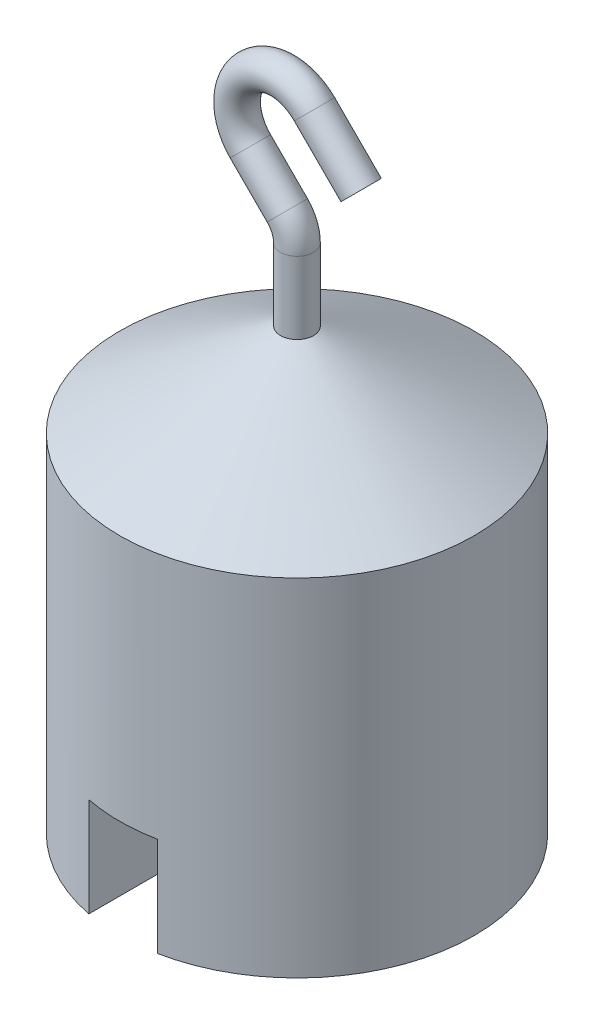
SolidWorks part; units mm, degrees
ref_plane "Front Plane" through (0, 0, 0) normal (0, 0, 1) x (1, 0, 0)
ref_plane "Top Plane" through (0, 0, 0) normal (0, 1, 0) x (1, 0, 0)
ref_plane "Right Plane" through (0, 0, 0) normal (1, 0, 0) x (0, 0, -1)
sketch "Sketch1" plane through (0, 0, 0) normal (0, 0, 1) x (1, 0, 0)
  line L0 (0, 0) -> (0, 42)
  line L1 (0, 42) -> (19.5, 53.2583)
  line L2 (19.5, 53.2583) -> (21.5, 53.2583)
  line L3 (21.5, 53.2583) -> (21.5, 0)
  line L4 (21.5, 0) -> (0, 0)
  dimension "D1" = 42
  dimension "D2" = 2
  dimension "D3" = 120
  dimension "D4" = 21.5
revolve "Revolve1" add sketch "Sketch1" angle 360 about L3
sketch "Sketch2" plane through (0, 53.2583, 0) normal (0, 1, 0) x (1, 0, 0)
  circle A0 centre (21.5, 0) radius 2
  dimension "D1" = 4
sketch "Sketch3" plane through (0, 0, 0) normal (0, 0, 1) x (1, 0, 0)
  line L0 (20.3284, 64.8299) -> (15.8431, 69.3152)
  line L1 (23.5, 53.2583) -> (19.5, 53.2583) construction
  line L2 (23.6213, 77.0934) -> (29.2782, 71.4365)
  line L3 (21.5, 53.2583) -> (21.5, 62.0015)
  arc A0 (15.8431, 69.3152) -> (23.6213, 77.0934) centre (19.7322, 73.2043) cw
  arc A1 (20.3284, 64.8299) -> (21.5, 62.0015) centre (17.5, 62.0015) cw
  point P12 (21.5, 63.6583)
  dimension "D3" = 5.5
  dimension "D6" = 4
  dimension "D1" = 45
  dimension "D2" = 8
  dimension "D4" = 8
  dimension "D5" = 10.4
sweep "Sweep6" add profiles "Sketch2" path "Sketch3"
sketch "Sketch10" plane through (0, 0, 0) normal (0, 0, 1) x (1, 0, 0)
  line L0 (0, 0) -> (43, 0) construction
  line L1 (17.35, 0) -> (25.65, 0)
  line L2 (17.35, 0) -> (17.35, 12)
  line L3 (17.35, 12) -> (25.65, 12)
  line L4 (25.65, 0) -> (25.65, 12)
  line L5 (21.5, 12) -> (21.5, 0) construction
  line L6 (0, 0) -> (43, 0) construction
  point P12 (21.5, 0)
  dimension "D1" = 12
  dimension "D2" = 8.3
extrude "Cut-Extrude1" cut sketch "Sketch10" against normal through all both and the other way through all
sketch "Sketch11" plane through (25.65, 0, 0) normal (-1, 0, 0) x (0, 0, 1)
  line L0 (0, -23.65) -> (0, 23.65) construction
  line L1 (-21.0957, 0) -> (21.0957, 0) construction
  circle A0 centre (0, 4.5) radius 1.5
  dimension "D1" = 3
  dimension "D2" = 4.5
extrude "Boss-Extrude1" add sketch "Sketch11" along normal up to next
sketch "Sketch12" plane through (0, 0, 0) normal (0, 0, 1) x (1, 0, 0)
  line L0 (23.5, 53.2583) -> (44.511, 74.2693) construction
  line L1 (23.5, 53.2583) -> (46.6392, 53.2583) construction
  dimension "D1" = 45
ref_plane "Plane1" through (0, 0, 0) normal (-1, 0, 0) x (0, 0, 1)
sketch "Sketch13" plane through (0, 0, 0) normal (-1, 0, 0) x (0, 0, 1)
  line L0 (0, 27) -> (0, 0) construction
  line L1 (-7.5, 33) -> (7.5, 33)
  line L2 (-7.5, 33) -> (-7.5, 27)
  line L3 (-7.5, 27) -> (7.5, 27)
  line L4 (7.5, 33) -> (7.5, 27)
  line L5 (21.5, 42) -> (-21.5, 42) construction
  dimension "D1" = 15
  dimension "D2" = 6
  dimension "D3" = 9
extrude "Cut-Extrude2" cut sketch "Sketch13" against normal blind 1.25
sketch "Sketch14" plane through (1.25, 0, 0) normal (-1, 0, 0) x (0, 0, 1)
  line L0 (-7.2241, 28) -> (7.2241, 28) construction
  line L1 (-7.2241, 28) -> (-7.2241, 27) construction
  line L2 (7.2241, 28) -> (7.2241, 27) construction
  line L3 (7.2241, 27) -> (-7.2241, 27) construction
  line L4 (4.3978, 29.2) -> (6.4889, 29.2) construction
  text T0 "500"
  text T1 "0" font "Century Gothic" height in points 8
  dimension "D1" = 1
  dimension "D2" = 1.2
extrude "Cut-Extrude3" cut sketch "Sketch14" against normal blind 0.5
